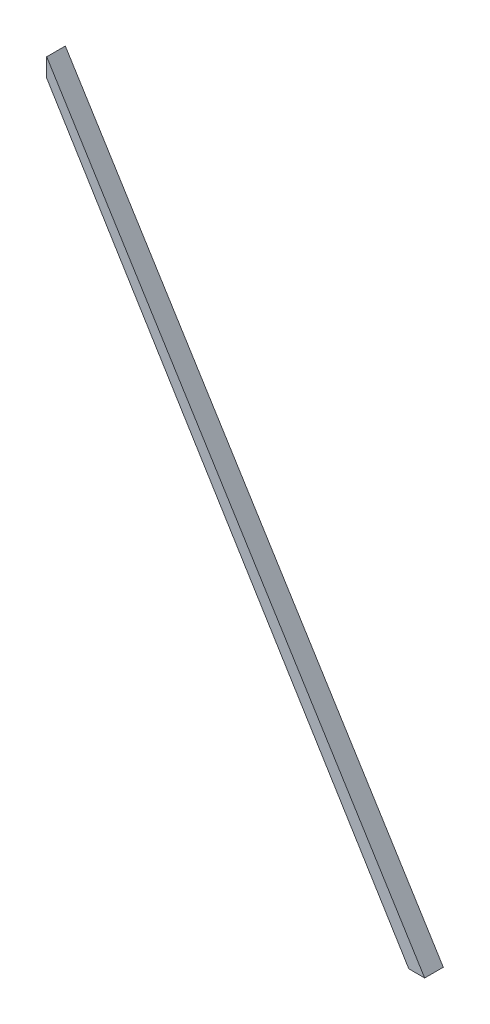
SolidWorks part; units mm, degrees
ref_plane "Front Plane" through (0, 0, 0) normal (0, 0, 1) x (1, 0, 0)
ref_plane "Top Plane" through (0, 0, 0) normal (0, 1, 0) x (1, 0, 0)
ref_plane "Right Plane" through (0, 0, 0) normal (1, 0, 0) x (0, 0, -1)
sketch "Sketch1" plane through (0, 0, 0) normal (0, 0, 1) x (1, 0, 0)
  line L0 (0, 0) -> (0, 830.58) construction
  line L1 (0, 0) -> (515.62, 0) construction
  line L2 (0, 830.58) -> (515.62, 0)
  line L3 (515.62, 0) -> (494.0402, -13.3967)
  line L4 (494.0402, -13.3967) -> (0, 782.4217)
  line L5 (0, 830.58) -> (0, 782.4217)
  dimension "D1" = 515.62
  dimension "D2" = 830.58
  dimension "D3" = 25.4
extrude "Boss-Extrude1" add sketch "Sketch1" against normal blind 25.4
sketch "Sketch2" plane through (0, 0, 0) normal (0, 0, 1) x (1, 0, 0)
  line L0 (515.62, 0) -> (485.7236, 0)
  line L1 (0, 782.4217) -> (494.0402, -13.3967) construction
  line L2 (485.7236, 0) -> (494.0402, -13.3967)
  line L3 (494.0402, -13.3967) -> (515.62, 0)
extrude "Cut-Extrude2" cut sketch "Sketch2" against normal blind 127
sketch "Sketch4" plane through (0, 0, -25.4) normal (0, 0, -1) x (-1, 0, 0)
  line L0 (0, 805.2817) -> (-493.9786, 0)
  line L1 (0, 830.58) -> (0, 782.4217) construction
  line L2 (-485.7236, 0) -> (-515.62, 0) construction
  line L3 (-493.9786, 0) -> (-485.7236, 0)
  line L4 (-485.7236, 0) -> (0, 782.4217)
  line L5 (0, 782.4217) -> (0, 805.2817)
  dimension "D1" = 22.86
extrude "Cut-Extrude3" cut sketch "Sketch4" against normal blind 127
